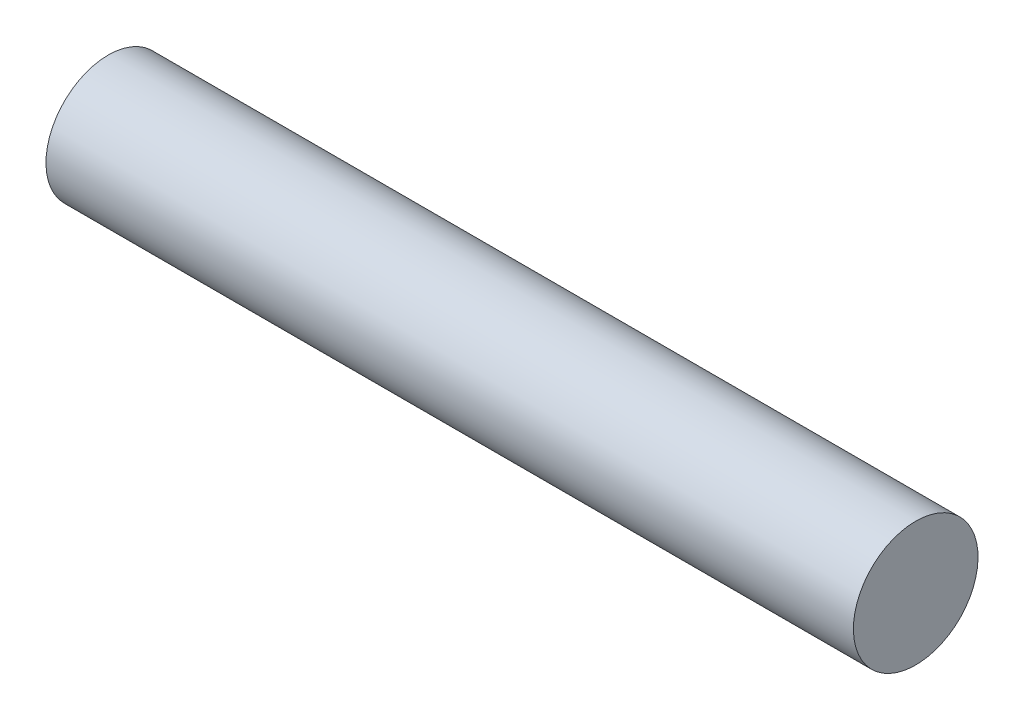
SolidWorks part; units mm, degrees
ref_plane "Plan de face" through (0, 0, 0) normal (0, 0, 1) x (1, 0, 0)
ref_plane "Plan de dessus" through (0, 0, 0) normal (0, 1, 0) x (1, 0, 0)
ref_plane "Plan de droite" through (0, 0, 0) normal (1, 0, 0) x (0, 0, -1)
sketch "Esquisse1" plane through (0, 0, 0) normal (0, 0, 1) x (1, 0, 0)
  line L0 (46, 0) -> (0, 0)
  line L1 (0, 0) -> (0, 3.55)
  line L2 (0, 3.55) -> (46, 3.55)
  line L3 (46, 3.55) -> (46, 0)
  dimension "D1" = 3.55
  dimension "D2" = 46
revolve "Révolution1" add sketch "Esquisse1" angle 360 about L0
ref_plane "Plan1" through (8, 0, 0) normal (1, 0, 0) x (0, 0, -1)
